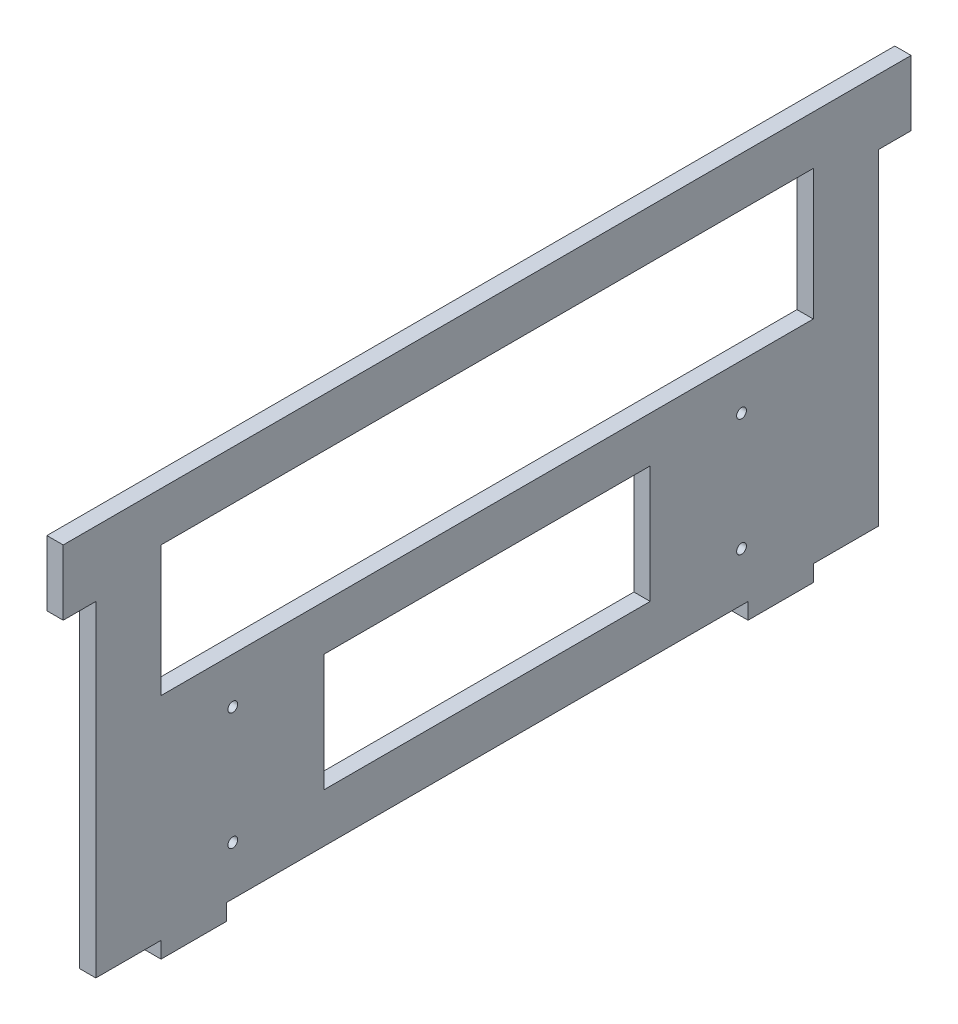
SolidWorks part; units mm, degrees
material "Perspex (TM) GS Acrylic Cast Sheet"
ref_plane "Ebene vorne" through (0, 0, 0) normal (0, 0, 1) x (1, 0, 0)
ref_plane "Ebene oben" through (0, 0, 0) normal (0, 1, 0) x (1, 0, 0)
ref_plane "Ebene rechts" through (0, 0, 0) normal (1, 0, 0) x (0, 0, -1)
sketch "Skizze2" plane through (0, 0, 0) normal (1, 0, 0) x (0, 0, -1)
  line L1 (-120, 60) -> (120, 60)
  line L2 (-120, 60) -> (-120, -60)
  line L3 (-120, -60) -> (120, -60)
  line L4 (120, 60) -> (120, -60)
  line L5 (-120, 60) -> (120, -60) construction
  line L6 (-120, -60) -> (120, 60) construction
  line L7 (-120, 60) -> (-130, 60)
  line L8 (-120, 60) -> (-120, 40)
  line L9 (-120, 40) -> (-130, 40)
  line L10 (-130, 60) -> (-130, 40)
  line L11 (-120, 60) -> (-130, 40) construction
  line L12 (-120, 40) -> (-130, 60) construction
  line L13 (120, 60) -> (130, 60)
  line L14 (120, 60) -> (120, 40)
  line L15 (120, 40) -> (130, 40)
  line L16 (130, 60) -> (130, 40)
  line L17 (120, 60) -> (130, 40) construction
  line L18 (120, 40) -> (130, 60) construction
  line L19 (100, -60) -> (80, -60)
  line L20 (100, -60) -> (100, -65)
  line L21 (100, -65) -> (80, -65)
  line L22 (80, -60) -> (80, -65)
  line L23 (-80, -60) -> (-100, -60)
  line L24 (-80, -60) -> (-80, -65)
  line L25 (-80, -65) -> (-100, -65)
  line L26 (-100, -60) -> (-100, -65)
  point P0 (0, 0)
  point P9 (-125, 50)
  point P13 (125, 50)
  dimension "D1" = 240
  dimension "D2" = 120
  dimension "D3" = 10
  dimension "D4" = 20
  dimension "D5" = 20
  dimension "D6" = 20
  dimension "D7" = 5
  dimension "D8" = 20
extrude "Aufsatz-Linear austragen1" add sketch "Skizze2" along normal blind 5
sketch "Skizze3" plane through (0, 0, 0) normal (-1, 0, 0) x (0, 0, 1)
  line L0 (0, -27) -> (0, 0) construction
  line L1 (-78, -9) -> (78, -9) construction
  line L2 (-78, -9) -> (-78, -45) construction
  line L3 (-78, -45) -> (78, -45) construction
  line L4 (78, -9) -> (78, -45) construction
  line L5 (-78, -9) -> (78, -45) construction
  line L6 (-78, -45) -> (78, -9) construction
  line L7 (80, -60) -> (-80, -60) construction
  line L8 (0, 0) -> (0, 25) construction
  line L9 (-50, -9) -> (50, -9)
  line L10 (-50, -9) -> (-50, -45)
  line L11 (-50, -45) -> (50, -45)
  line L12 (50, -9) -> (50, -45)
  line L13 (-50, -9) -> (50, -45) construction
  line L14 (-50, -45) -> (50, -9) construction
  line L15 (130, 60) -> (-130, 60) construction
  line L16 (-100, 45) -> (100, 45)
  line L17 (-100, 45) -> (-100, 5)
  line L18 (-100, 5) -> (100, 5)
  line L19 (100, 45) -> (100, 5)
  line L20 (-100, 45) -> (100, 5) construction
  line L21 (-100, 5) -> (100, 45) construction
  circle A0 centre (-78, -9) radius 1.5
  circle A1 centre (78, -45) radius 1.5
  circle A2 centre (-78, -45) radius 1.5
  circle A3 centre (78, -9) radius 1.5
  point P0 (0, -27)
  dimension "D1" = 3
  dimension "D2" = 156
  dimension "D3" = 36
  dimension "D4" = 15
  dimension "D5" = 100
  dimension "D6" = 40
  dimension "D7" = 15
  dimension "D8" = 200
extrude "Schnitt-Linear austragen1" cut sketch "Skizze3" against normal through all
